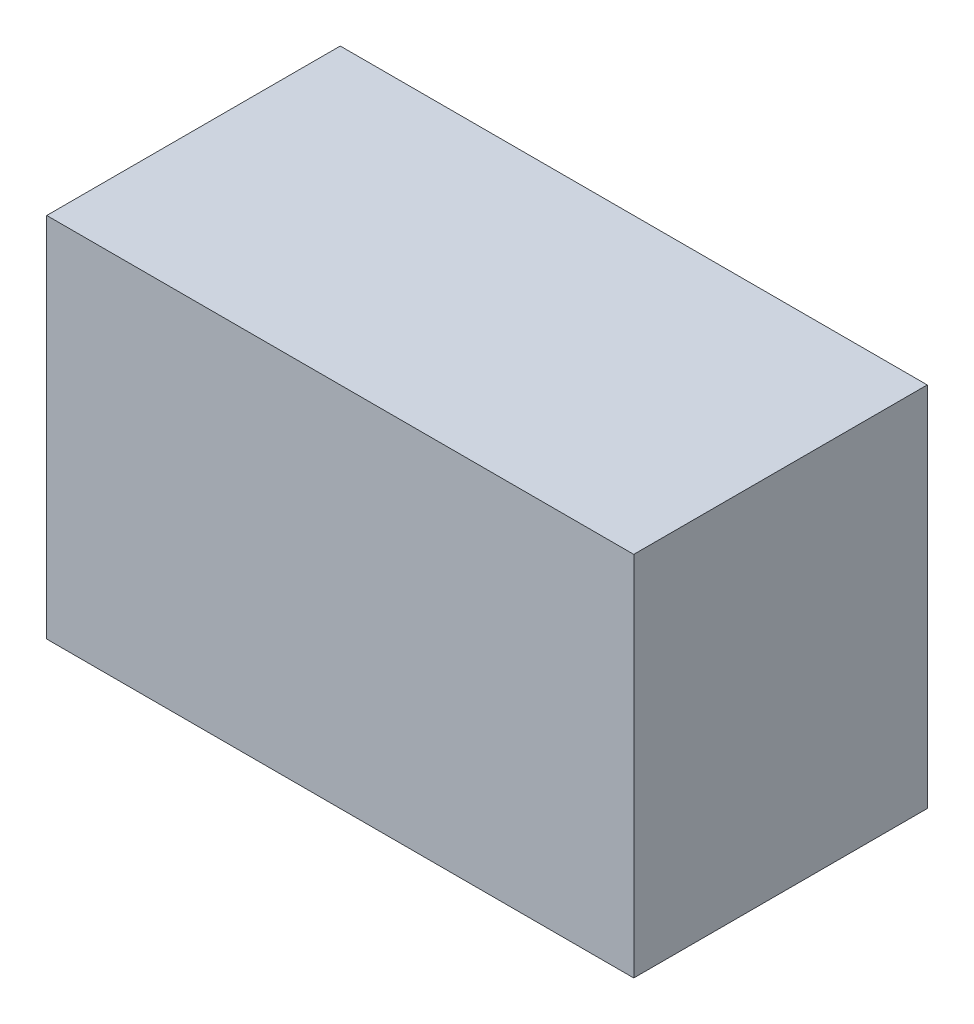
SolidWorks part; units mm, degrees
material "Malleable Cast Iron"
ref_plane "Front Plane" through (0, 0, 0) normal (0, 0, 1) x (1, 0, 0)
ref_plane "Top Plane" through (0, 0, 0) normal (0, 1, 0) x (1, 0, 0)
ref_plane "Right Plane" through (0, 0, 0) normal (1, 0, 0) x (0, 0, -1)
sketch "Sketch1" plane through (0, 0, 0) normal (0, 1, 0) x (1, 0, 0)
  line L1 (0, 0) -> (2032, 0)
  line L2 (0, 0) -> (0, 1016)
  line L3 (0, 1016) -> (2032, 1016)
  line L4 (2032, 0) -> (2032, 1016)
  dimension "D1" = 2032
  dimension "D2" = 1016
extrude "Extrude1" add sketch "Sketch1" along normal blind 1270
